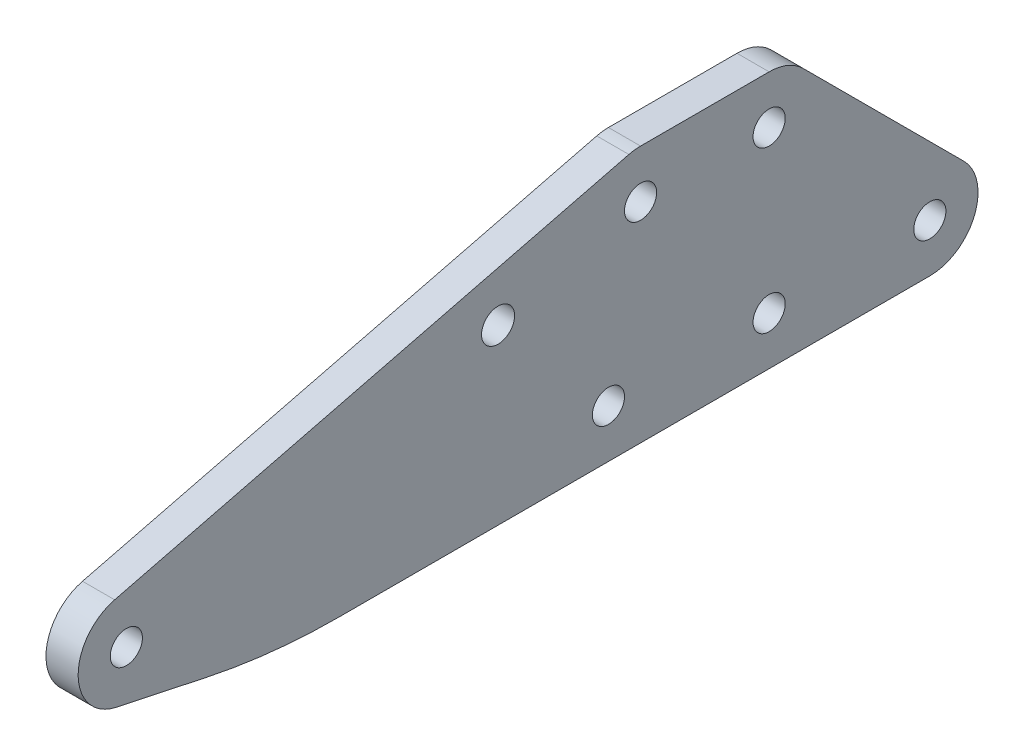
SolidWorks part; units mm, degrees
ref_plane "Front Plane" through (0, 0, 0) normal (0, 0, 1) x (1, 0, 0)
ref_plane "Top Plane" through (0, 0, 0) normal (0, 1, 0) x (1, 0, 0)
ref_plane "Right Plane" through (0, 0, 0) normal (1, 0, 0) x (0, 0, -1)
sketch "Sketch1" plane through (0, 0, 0) normal (1, 0, 0) x (0, 0, -1)
  line L0 (31.75, 95.375) -> (-84.7785, 95.375)
  line L2 (-128.9804, 101.9331) -> (-111.1833, 98.1503)
  line L3 (0, 111.25) -> (-127, 111.25) construction
  line L4 (38.4852, 111.6352) -> (6.7352, 143.3852)
  line L5 (-51.3017, 85.85) -> (-51.3017, -66.8)
  line L6 (-51.3017, -66.8) -> (51.3017, -66.8)
  line L7 (51.3017, -66.8) -> (51.3017, 85.85)
  line L8 (51.3017, 85.85) -> (24.6566, 193.5501)
  line L9 (-24.6566, 193.5501) -> (-51.3017, 85.85)
  line L10 (-51.3017, 85.85) -> (-51.3017, -66.8) construction
  line L11 (-51.3017, -66.8) -> (51.3017, -66.8) construction
  line L12 (51.3017, -66.8) -> (51.3017, 85.85) construction
  line L13 (51.3017, 85.85) -> (24.6566, 193.5501) construction
  line L14 (-24.6566, 193.5501) -> (-51.3017, 85.85) construction
  line L16 (0, 136.65) -> (-25.4, 136.65) construction
  line L51 (31.75, 104.9) -> (-31.75, 104.9) construction
  line L52 (0, 0) -> (0, 104.9) construction
  line L53 (0, 187.45) -> (0, 136.65) construction
  line L54 (-129.3102, 120.4906) -> (-27.7102, 145.8906)
  line L55 (0, 146.175) -> (-25.4, 146.175)
  circle A0 centre (-127, 111.25) radius 3.175
  arc A1 (24.6566, 193.5501) -> (-24.6566, 193.5501) centre (0, 187.45) ccw
  arc A2 (24.6566, 193.5501) -> (-24.6566, 193.5501) centre (0, 187.45) ccw construction
  arc A3 (-129.3102, 120.4906) -> (-128.9804, 101.9331) centre (-127, 111.25) ccw
  circle A4 centre (-53.5582, 129.6105) radius 3.2639
  arc A10 (38.4852, 111.6352) -> (31.75, 95.375) centre (31.75, 104.9) cw
  arc A15 (6.7352, 143.3852) -> (0, 146.175) centre (0, 136.65) ccw
  arc A16 (-111.1833, 98.1503) -> (-84.7785, 95.375) centre (-84.7785, 222.375) ccw
  circle A17 centre (0, 136.65) radius 3.175
  circle A18 centre (-31.75, 104.9) radius 3.175
  circle A19 centre (0, 104.9) radius 3.175
  circle A20 centre (31.75, 104.9) radius 3.175
  circle A28 centre (0, 187.45) radius 14.2875 construction
  circle A29 centre (0, 187.45) radius 14.2875 construction
  arc A30 (-25.4, 146.175) -> (-27.7102, 145.8906) centre (-25.4, 136.65) ccw
  circle A31 centre (-25.4, 136.65) radius 3.175
  point P0 (-127, 111.25)
  dimension "D2" = 6.35
  dimension "D3" = 6.35
  dimension "D4" = 9.525
  dimension "D5" = 127
  dimension "D6" = 12
  dimension "D7" = 6.35
  dimension "D10" = 6.35
  dimension "D13" = 6.5278
  dimension "D8" = 50.8
  dimension "D9" = 31.75
  dimension "D11" = 25.4
  dimension "D12" = 63.5
  dimension "D14" = 9.525
  dimension "D15" = 12.7
  dimension "D1" = 0
extrude "Boss-Extrude1" add sketch "Sketch1" against normal blind 6.35 from surface at -47.625
